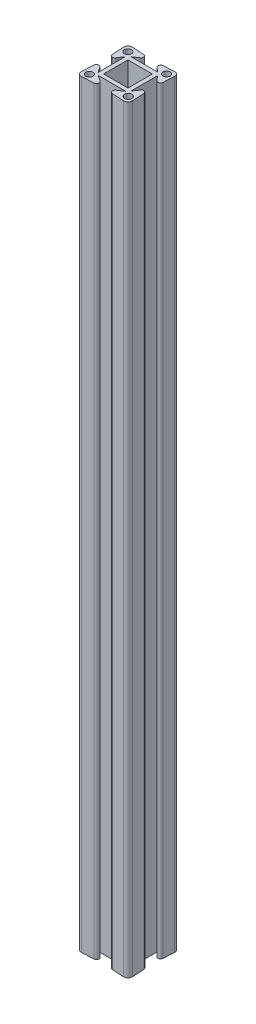
SolidWorks part; units mm, degrees
ref_plane "Front Plane" through (0, 0, 0) normal (0, 0, 1) x (1, 0, 0)
ref_plane "Top Plane" through (0, 0, 0) normal (0, 1, 0) x (1, 0, 0)
ref_plane "Right Plane" through (0, 0, 0) normal (1, 0, 0) x (0, 0, -1)
sketch "Sketch1" plane through (0, 0, 0) normal (0, 1, 0) x (1, 0, 0)
  line L1 (-16.2586, 10.8064) -> (9.1414, 10.8064)
  line L2 (-16.2586, 10.8064) -> (-16.2586, -14.5936)
  line L3 (-16.2586, -14.5936) -> (9.1414, -14.5936)
  line L4 (9.1414, 10.8064) -> (9.1414, -14.5936)
  dimension "D1" = 25.4
  dimension "D2" = 25.4
sketch "Sketch2" plane through (0, 0, 0) normal (0, 1, 0) x (1, 0, 0)
  line L0 (-19.5248, -1.8997) -> (12.956, -1.8997)
  line L1 (-3.2844, -16.3317) -> (-3.2844, 12.7118)
  line L2 (-16.2586, -14.5936) -> (9.1414, 10.8064)
  line L3 (-16.2586, 10.8064) -> (9.1414, -14.5936)
  line L4 (-16.2586, -14.5936) -> (-15.6079, -2.6453)
  line L8 (-1.665, 10.1557) -> (9.1414, 10.8064)
  line L9 (-16.2586, -14.5936) -> (-4.3104, -13.9428)
  line L10 (-4.3104, -13.9428) -> (-10.3408, -9.862)
  line L11 (-15.6079, -2.6453) -> (-11.6319, -8.6265)
  line L13 (8.4906, 0) -> (9.1414, 10.8064)
  line L16 (-4.2921, 10.1557) -> (-16.2586, 10.8064)
  line L18 (-2.8545, -13.9363) -> (9.1414, -14.5936)
  line L19 (8.4841, -2.5977) -> (4.4616, -8.4759)
  line L20 (-15.6079, -1.1601) -> (-11.6319, 4.8561)
  line L21 (-2.8545, -13.9363) -> (3.3396, -9.862)
  line L22 (-15.6079, -1.1601) -> (-16.2586, 10.8064)
  line L23 (8.4841, -2.5977) -> (9.1414, -14.5936)
  line L25 (8.4906, 0) -> (4.4616, 4.6752)
  line L26 (4.4616, -9.862) -> (-11.6319, -9.862)
  line L27 (4.4616, -9.862) -> (4.4616, 6.2316)
  line L28 (4.4616, 6.2316) -> (-11.6319, 6.2316)
  line L29 (-11.6319, -9.862) -> (-11.6319, 6.2316)
  line L30 (-1.665, 10.1557) -> (3.012, 6.2316)
  line L31 (-4.2921, 10.1557) -> (-10.2576, 6.2316)
  line L32 (3.1916, -8.592) -> (3.1916, 4.9616)
  line L33 (3.1916, 4.9616) -> (-10.3619, 4.9616)
  line L34 (-10.3619, -8.592) -> (-10.3619, 4.9616)
  line L35 (3.1916, -8.592) -> (-10.3619, -8.592)
  line L36 (4.4616, -8.4759) -> (3.3396, -9.862)
  line L37 (-10.3408, -9.862) -> (-11.6319, -8.6265)
  line L38 (4.4616, 4.6752) -> (3.012, 6.2316)
  line L39 (-10.2576, 6.2316) -> (-11.6319, 4.8561)
  dimension "D1" = 1.27
extrude "Boss-Extrude1" add sketch "Sketch2" along normal blind 375
fillet "Fillet1" radius 2.032 4 edges at (9.1414, 187.5, 14.5936) (9.1414, 187.5, -10.8064) (-16.2586, 187.5, -10.8064) (-16.2586, 187.5, 14.5936)
fillet "Fillet2" radius 1.27 8 edges at (-15.6079, 187.5, 2.6453) (-15.6079, 187.5, 1.1601) (-4.3104, 187.5, 13.9428) (-4.2921, 187.5, -10.1557) (-1.665, 187.5, -10.1557) (8.4906, 187.5, 0) (8.4841, 187.5, 2.5977) (-2.8545, 187.5, 13.9363)
sketch "Sketch5" plane through (0, 375, 0) normal (0, 1, 0) x (1, 0, 0)
  line L1 (2.4309, 4.0973) -> (-9.6178, 4.0973)
  line L2 (2.4309, 4.0973) -> (2.4309, -7.8996)
  line L3 (2.4309, -7.8996) -> (-9.6178, -7.8996)
  line L4 (-9.6178, 4.0973) -> (-9.6178, -7.8996)
  circle A0 centre (5.9214, 7.6654) radius 1.7848
  circle A1 centre (6.0507, -11.416) radius 1.8099
  circle A2 centre (-13.1083, 7.6137) radius 1.778
  circle A3 centre (-13.0307, -11.5453) radius 1.778
extrude "Cut-Extrude3" cut sketch "Sketch5" against normal through all contours L1 L4 L3 L2 | A1 | A3 | A2 | A0
scale "Scale1" bodies to scale 124 scale about centroid uniform scaling yes scale factor 0.8
